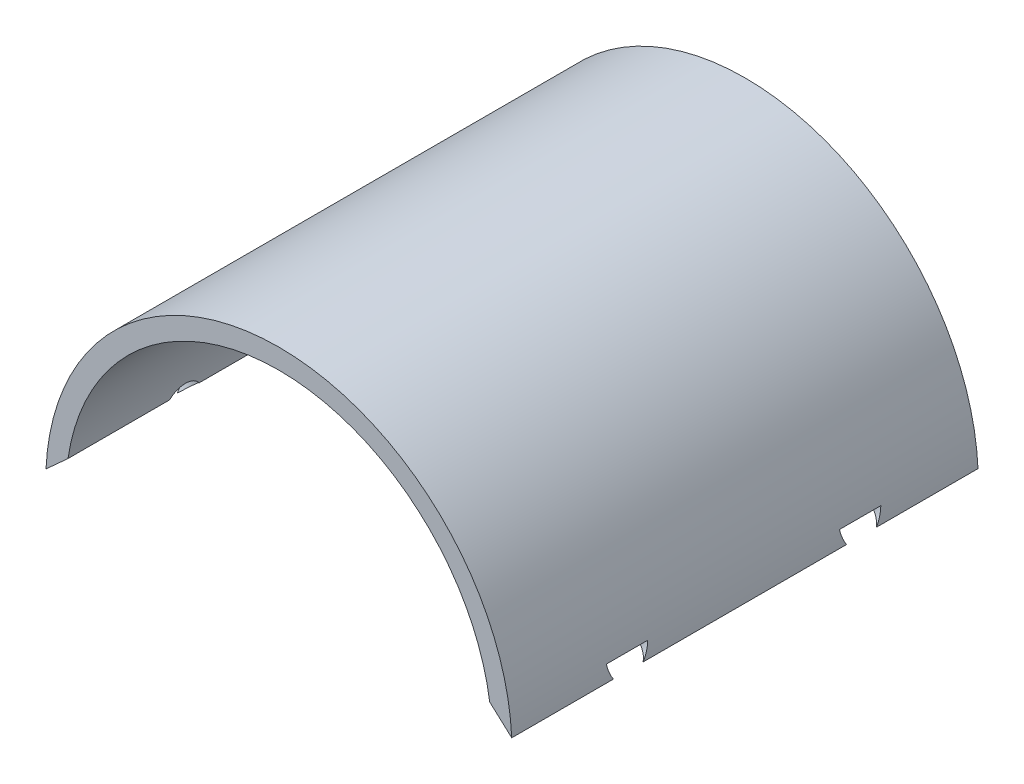
SolidWorks part; units mm, degrees
ref_plane "Front Plane" through (0, 0, 0) normal (0, 0, 1) x (1, 0, 0)
ref_plane "Top Plane" through (0, 0, 0) normal (0, 1, 0) x (1, 0, 0)
ref_plane "Right Plane" through (0, 0, 0) normal (1, 0, 0) x (0, 0, -1)
sketch "Sketch1" plane through (0, 0, 0) normal (0, 0, 1) x (1, 0, 0)
  line L0 (0, 0) -> (0, 44.45) construction
  line L1 (-40.2039, 5.9378) -> (40.2039, 5.9378) construction
  line L2 (-44.399, 2.1278) -> (44.399, 2.1278) construction
  line L3 (-40.2039, 5.9378) -> (-44.399, 2.1278)
  line L4 (40.2039, 5.9378) -> (44.399, 2.1278)
  arc A0 (44.399, 2.1278) -> (-44.399, 2.1278) centre (0, 0) ccw
  arc A1 (40.2039, 5.9378) -> (-40.2039, 5.9378) centre (0, 0) ccw
  dimension "D1" = 88.9
  dimension "D2" = 3.81
  dimension "D3" = 3.81
extrude "Boss-Extrude1" add sketch "Sketch1" along normal blind 88.9
sketch "Sketch2" plane through (-21.1272, 23.263, 0) normal (0.6723, -0.7403, 0) x (0.7403, 0.6723, 0)
  line L0 (-28.6033, 88.9) -> (-28.6033, 0.1046) construction
  line L1 (-31.4368, 88.9) -> (-25.7698, 88.9) construction
  line L2 (-31.4368, 44.45) -> (-25.7698, 44.45) construction
  line L3 (-31.4368, 88.9) -> (-31.4368, 0) construction
  line L4 (-25.7698, 88.9) -> (-25.7698, 0) construction
  circle A0 centre (-28.6033, 66.7273) radius 4
  circle A1 centre (-28.6033, 22.1727) radius 4
  point P12 (-28.6033, 44.5023)
  dimension "D1" = 8
  dimension "D2" = 22.225
extrude "Cut-Extrude1" cut sketch "Sketch2" against normal blind 2
sketch "Sketch3" plane through (21.1272, 23.263, 0) normal (-0.6723, -0.7403, 0) x (0.7403, -0.6723, 0)
  line L0 (28.6033, 88.9) -> (28.6033, 0) construction
  line L1 (25.7698, 88.9) -> (31.4368, 88.9) construction
  line L2 (25.7698, 0) -> (31.4368, 0) construction
  line L3 (25.7698, 44.45) -> (31.4368, 44.45) construction
  line L4 (25.7698, 88.9) -> (25.7698, 0) construction
  line L5 (31.4368, 88.9) -> (31.4368, 0) construction
  circle A0 centre (28.6033, 66.675) radius 4
  circle A1 centre (28.6033, 22.225) radius 4
  dimension "D1" = 8
  dimension "D2" = 22.225
extrude "Cut-Extrude2" cut sketch "Sketch3" against normal blind 2
